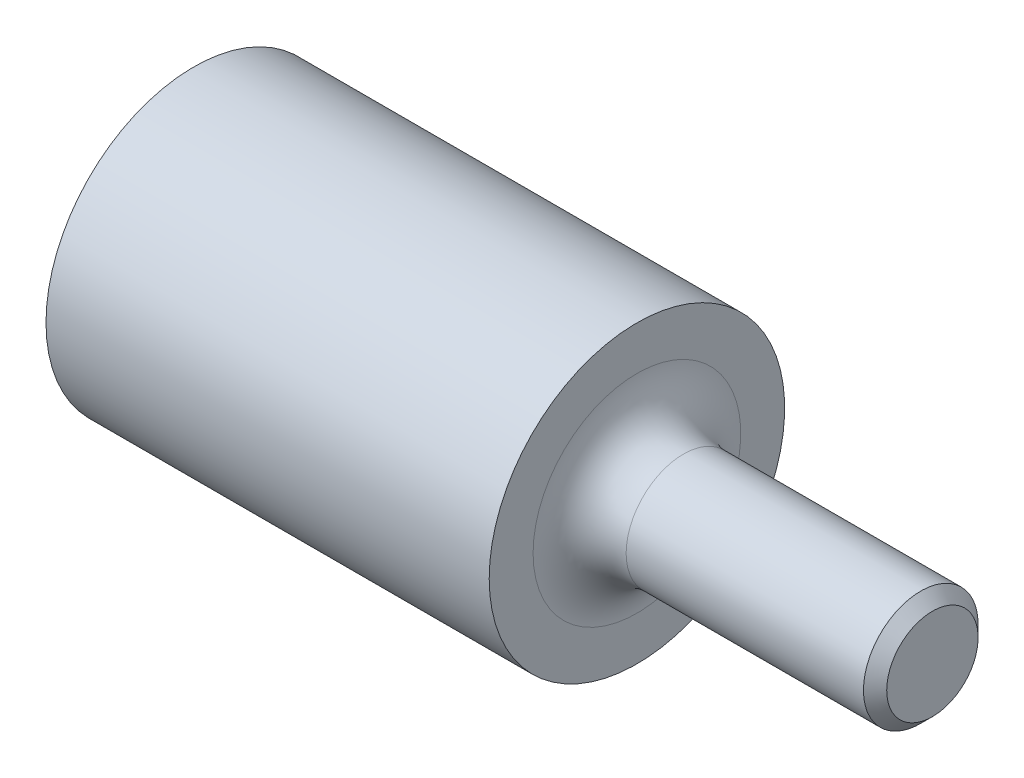
SolidWorks part; units mm, degrees
material "ABS"
ref_plane "Plan de face" through (0, 0, 0) normal (0, 0, 1) x (1, 0, 0)
ref_plane "Plan de dessus" through (0, 0, 0) normal (0, 1, 0) x (1, 0, 0)
ref_plane "Plan de droite" through (0, 0, 0) normal (1, 0, 0) x (0, 0, -1)
sketch "Esquisse3" plane through (0, 0, 0) normal (0, 1, 0) x (1, 0, 0)
  line L1 (0, 6.35) -> (19.05, 6.35)
  line L2 (19.05, 6.35) -> (19.05, 2.4638)
  line L3 (19.05, 2.4638) -> (31.75, 2.4638)
  line L4 (31.75, 2.4638) -> (31.75, 0)
  line L6 (0, 6.35) -> (0, 0)
  line L9 (0, 0) -> (31.75, 0)
  dimension "D1" = 19.05
  dimension "D2" = 12.7
  dimension "D3" = 6.35
  dimension "D6" = 2.4638
revolve "Révolution1" add sketch "Esquisse3" angle 360 about L9
fillet "Congé1" radius 2 1 edges at (19.05, 0, 2.4638)
sketch "Esquisse4" plane through (0, 0, 0) normal (-1, 0, 0) x (0, 0, 1)
  line L0 (2.794, -1.508) -> (2.794, 1.508)
  arc A0 (2.794, 1.508) -> (2.794, -1.508) centre (0, 0) ccw
  dimension "D1" = 6.35
  dimension "D2" = 2.794
extrude "Enlèv. mat.-Extru.1" cut sketch "Esquisse4" against normal blind 15.875
chamfer "Chanfrein1" distance 0.5 angle 45 1 edges at (31.75, 0, 2.4638)
